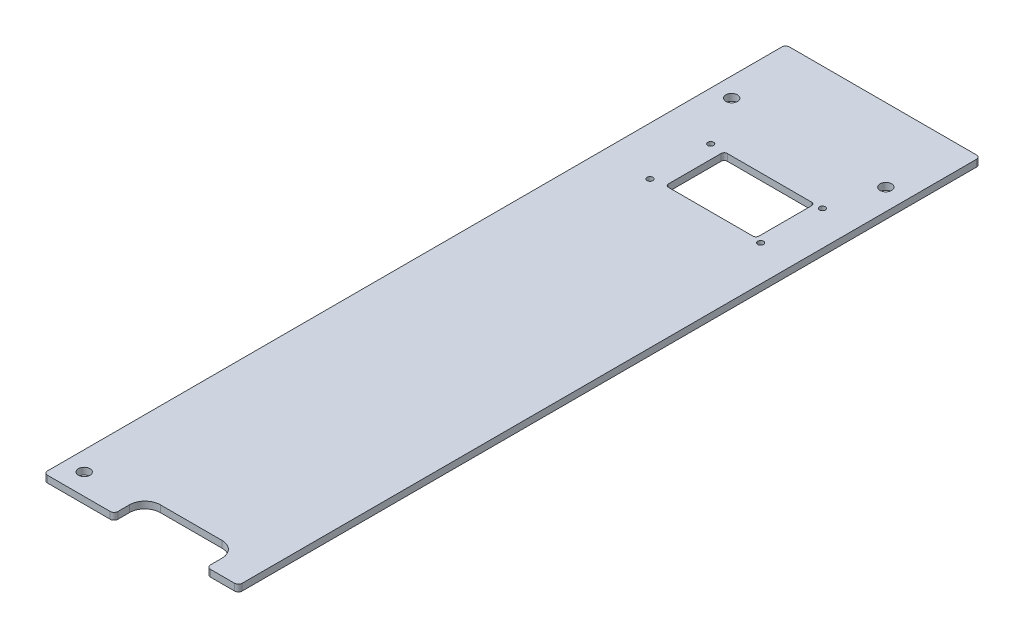
SolidWorks part; units mm, degrees
material "Acrylic (Medium-high impact)"
ref_plane "Front Plane" through (0, 0, 0) normal (0, 0, 1) x (1, 0, 0)
ref_plane "Top Plane" through (0, 0, 0) normal (0, 1, 0) x (1, 0, 0)
ref_plane "Right Plane" through (0, 0, 0) normal (1, 0, 0) x (0, 0, -1)
sketch "Sketch1" plane through (0, 0, 0) normal (0, 1, 0) x (1, 0, 0)
  line L1 (-80.1688, -305.5938) -> (80.1687, -305.5938)
  line L2 (-80.1688, -305.5938) -> (-80.1688, 305.5938)
  line L3 (-80.1688, 305.5938) -> (80.1687, 305.5938)
  line L4 (80.1687, -305.5938) -> (80.1687, 305.5938)
  line L5 (-80.1688, -305.5938) -> (80.1687, 305.5938) construction
  line L6 (-80.1688, 305.5938) -> (80.1687, -305.5938) construction
  point P0 (0, 0)
  dimension "D1" = 160.3375
  dimension "D2" = 611.1875
extrude "Boss-Extrude1" add sketch "Sketch1" along normal blind 5.588
fillet "Fillet1" radius 3.175 4 edges at (80.1687, 2.794, 305.5938) (-80.1688, 2.794, 305.5938) (80.1687, 2.794, -305.5938) (-80.1688, 2.794, -305.5938)
sketch "Sketch2" plane through (0, 5.588, 0) normal (0, 1, 0) x (1, 0, 0)
  line L0 (80.1687, -302.4187) -> (80.1687, 302.4188) construction
  line L1 (76.9937, 305.5938) -> (-76.9938, 305.5938) construction
  line L2 (-64.2938, 245.2688) -> (62.7062, 245.2688) construction
  line L3 (62.7062, 245.2688) -> (62.7063, -288.1312) construction
  line L4 (62.7063, -288.1312) -> (-64.2937, -288.1312) construction
  circle A0 centre (62.7062, 245.2688) radius 4.7625
  circle A1 centre (-64.2938, 245.2688) radius 4.7625
  circle A2 centre (62.7063, -288.1312) radius 4.7625 construction
  circle A3 centre (-64.2937, -288.1312) radius 4.7625
  dimension "D1" = 17.4625
  dimension "D3" = 9.525
  dimension "D4" = 9.525
  dimension "D6" = 9.525
  dimension "D7" = 9.525
  dimension "D2" = 60.325
  dimension "D5" = 127
  dimension "D8" = 127
  dimension "D9" = 533.4
extrude "Cut-Extrude1" cut sketch "Sketch2" against normal blind 6.35
sketch "Sketch3" plane through (0, 5.588, 0) normal (0, 1, 0) x (1, 0, 0)
  line L0 (-76.9938, -305.5938) -> (76.9937, -305.5938) construction
  line L1 (-48.4188, -305.5938) -> (-80.1688, -305.5938) construction
  line L2 (-48.4188, -305.5938) -> (-48.4188, 305.5938) construction
  line L3 (-48.4188, 305.5938) -> (-80.1688, 305.5938) construction
  line L4 (-80.1688, -305.5938) -> (-80.1688, 305.5938) construction
  line L5 (-80.1688, 302.4188) -> (-80.1688, -302.4187) construction
  line L6 (76.9937, 305.5938) -> (-76.9938, 305.5938) construction
  line L8 (-22.225, -305.5938) -> (53.975, -305.5938)
  line L9 (-22.225, -305.5938) -> (-22.225, -280.1938)
  line L10 (-22.225, -280.1938) -> (53.975, -280.1938)
  line L11 (53.975, -305.5938) -> (53.975, -280.1938)
  line L12 (-22.225, -280.1938) -> (-48.4188, -280.1938) construction
  line L13 (53.975, -280.1938) -> (80.1687, -280.1938) construction
  line L14 (80.1687, -302.4187) -> (80.1687, 302.4188) construction
  dimension "D1" = 31.75
  dimension "D2" = 76.2
  dimension "D3" = 25.4
extrude "Cut-Extrude2" cut sketch "Sketch3" against normal blind 6.35
fillet "Fillet2" radius 3.175 2 edges at (53.975, 2.794, 305.5938) (-22.225, 2.794, 305.5938)
fillet "Fillet3" radius 12.7 2 edges at (53.975, 2.794, 280.1938) (-22.225, 2.794, 280.1938)
sketch "Sketch4" plane through (0, 5.588, 0) normal (0, 1, 0) x (1, 0, 0)
  line L3 (-51.2763, 296.0688) -> (-51.2763, -504.0312) construction
  line L4 (76.9937, 305.5938) -> (-76.9938, 305.5938) construction
  line B0 (-26.6383, 203.9938) -> (42.8393, 203.9938)
  line B1 (-29.1783, 201.4537) -> (-29.1783, 158.115)
  line B2 (-26.6383, 155.575) -> (42.8393, 155.575)
  line B3 (45.3793, 201.4537) -> (45.3793, 158.115)
  arc B4 (42.8393, 155.575) -> (45.3793, 158.115) centre (42.8393, 158.115) ccw
  arc B5 (-29.1783, 158.115) -> (-26.6383, 155.575) centre (-26.6383, 158.115) ccw
  arc B6 (-26.6383, 203.9938) -> (-29.1783, 201.4537) centre (-26.6383, 201.4538) ccw
  arc B7 (42.8393, 203.9938) -> (45.3793, 201.4537) centre (42.8393, 201.4538) cw
  circle B8 centre (-40.2908, 203.9938) radius 2.3813
  circle B9 centre (-40.2908, 153.9558) radius 2.3813
  circle B10 centre (51.7451, 203.9938) radius 2.3813
  circle B11 centre (50.8952, 153.9557) radius 2.3813
  dimension "D1" = 22.098
  dimension "D2" = 101.6
sketch_block_instance "Block1-1"
sketch_block "Block1" parameters "D3"=2.54, "D4"=4.7625, "D6"=4.7625, "D9"=4.7625, "D10"=4.7625, "D1"=88.9, "D2"=48.4187, "D5"=11.1125, "D7"=50.038, "D8"=6.35, "D11"=50.038, "D12"=91.186
extrude "Cut-Extrude3" cut sketch "Sketch4" against normal blind 25.4
sketch "Sketch5" plane through (0, 5.588, 0) normal (0, 1, 0) x (1, 0, 0)
  line L0 (-29.1783, 179.7844) -> (-29.1783, -55.7912) construction
  line L1 (-29.1783, 201.4537) -> (-29.1783, 158.115) construction
  line L2 (-29.1783, 53.975) -> (51.6756, 53.975) construction
  line L3 (-26.6383, 155.575) -> (42.8393, 155.575) construction
  dimension "D1" = 101.6
